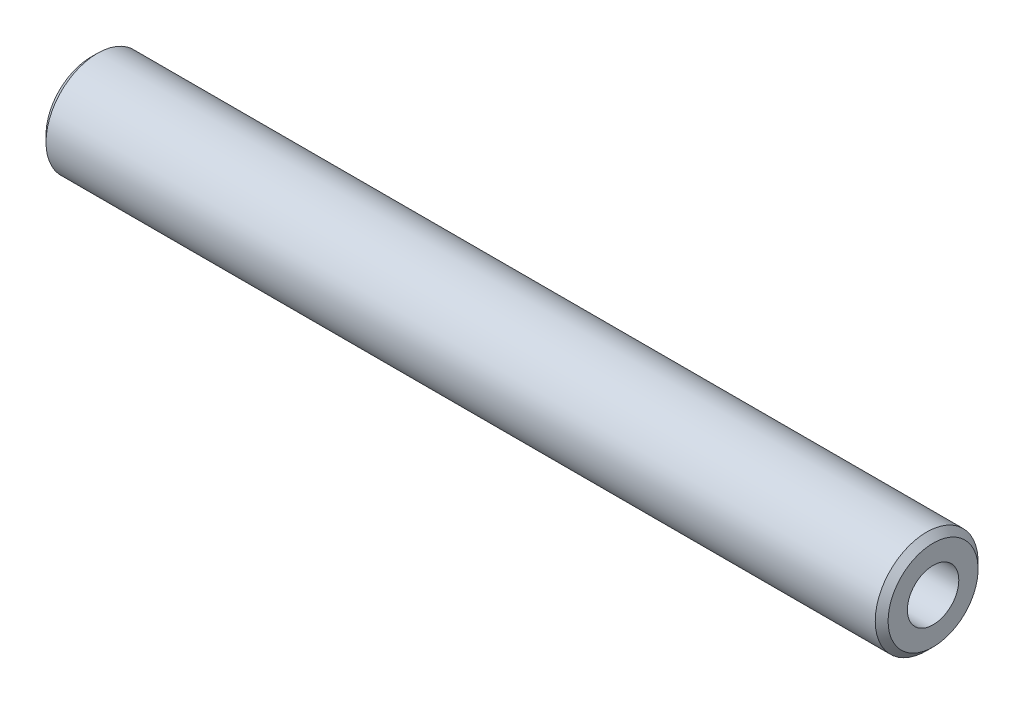
SolidWorks part; units mm, degrees
material "1.4301 (X5CrNi18-10)"
ref_plane "正面" through (0, 0, 0) normal (0, 0, 1) x (1, 0, 0)
ref_plane "平面" through (0, 0, 0) normal (0, 1, 0) x (1, 0, 0)
ref_plane "右側面" through (0, 0, 0) normal (1, 0, 0) x (0, 0, -1)
sketch "ｽｹｯﾁ1" plane through (0, 0, 0) normal (0, 0, 1) x (1, 0, 0)
  line L0 (0, 0) -> (21203.2319, 0) construction
  line L2 (-32.75, 0) -> (32.75, 0)
  line L3 (-32.75, 0) -> (-32.75, 4)
  line L4 (-32.75, 4) -> (32.75, 4)
  line L5 (32.75, 0) -> (32.75, 4)
  point P7 (0, 0)
  dimension "D1" = 8
  dimension "D2" = 65.5
revolve "回転1" add sketch "ｽｹｯﾁ1" angle 360 about L0
hole_wizard "M4x0.7 ねじ穴1" positions "3Dｽｹｯﾁ1" profile "ｽｹｯﾁ3" tap size "M4x0.7" standard "JIS"
sketch3d "3Dｽｹｯﾁ1"
  line L0 (32.75, 0, 0) -> (-32.75, 0, 0) construction
  point P0 (32.75, 0, 0)
  point P4 (-32.75, 0, 0)
sketch "ｽｹｯﾁ3" plane through (32.75, 0, 0) normal (0, 1, 0) x (0, 0, -1)
  line L0 (0, 0) -> (0, 12.4914)
  line L1 (0, 12.4914) -> (1.65, 11.5)
  line L2 (1.65, 11.5) -> (1.65, 8)
  line L3 (1.65, 8) -> (2, 8)
  line L4 (2, 8) -> (2, 0)
  line L5 (2, 0) -> (0, 0)
  line L10 (0, 12.4914) -> (-1.65, 11.5) construction
  line L11 (0, -6.35) -> (0, 107.95) construction
  dimension "ねじ下穴ﾄﾞﾘﾙ直径" = 3.3
  dimension "ねじ下穴ﾄﾞﾘﾙの深さ" = 11.5
  dimension "ねじ山の主要直径" = 4
  dimension "ねじ山の深さ" = 8
  dimension "ﾄﾞﾘﾙ角度" = 118
chamfer "面取り1" distance 0.5 angle 45 2 edges at (-32.75, 0, 4) (32.75, 0, 4)
